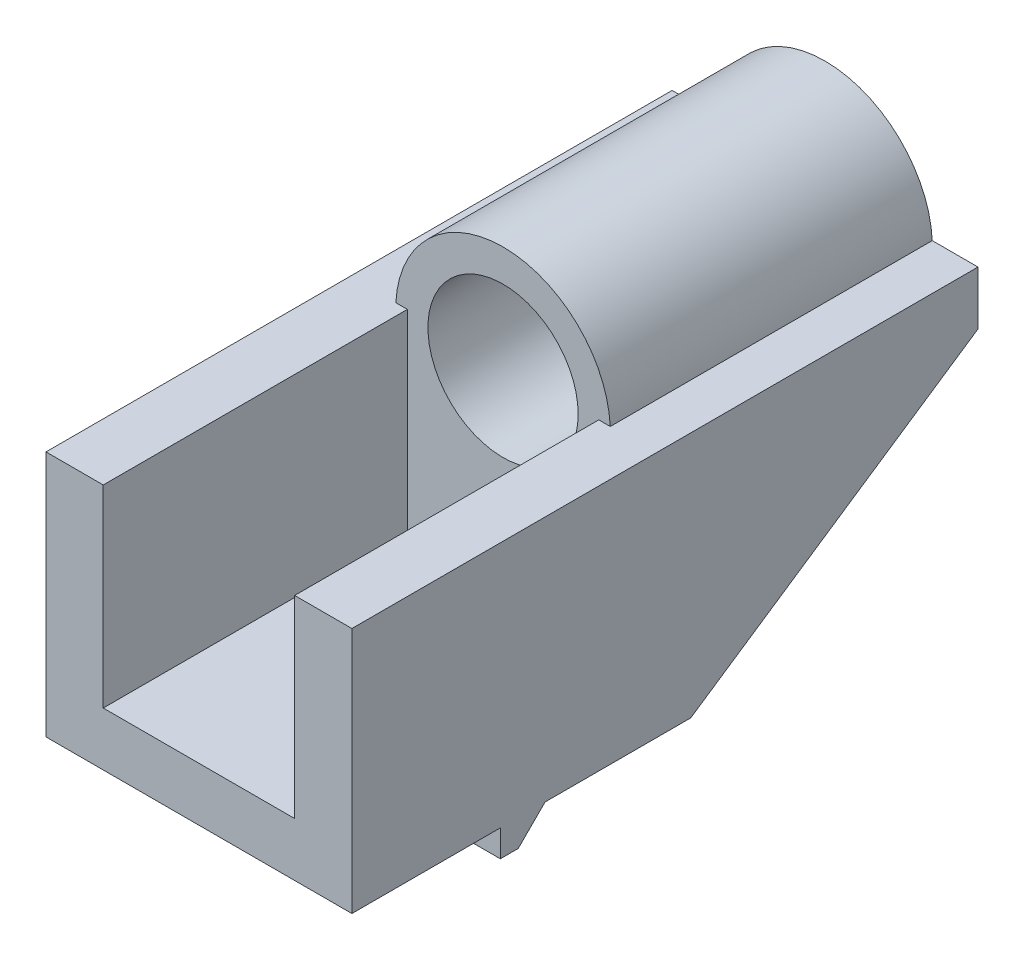
SolidWorks part; units mm, degrees
material "ABS"
ref_plane "Front Plane" through (0, 0, 0) normal (0, 0, 1) x (1, 0, 0)
ref_plane "Top Plane" through (0, 0, 0) normal (0, 1, 0) x (1, 0, 0)
ref_plane "Right Plane" through (0, 0, 0) normal (1, 0, 0) x (0, 0, -1)
sketch "Sketch1" plane through (0, 0, 0) normal (1, 0, 0) x (0, 0, -1)
  line L0 (0, 0) -> (0, -3)
  line L1 (0, -3) -> (-16.0587, -13.8)
  line L2 (-16.0587, -13.8) -> (-35, -13.8)
  line L3 (-35, -13.8) -> (-35, 0)
  line L4 (-35, 0) -> (0, 0)
  dimension "D1" = 35
  dimension "D2" = 3
  dimension "D3" = 13.8
  dimension "D4" = 18.9413
extrude "Boss-Extrude1" add sketch "Sketch1" along normal mid plane 17.1
sketch "Sketch2" plane through (0, 0, 35) normal (0, 0, 1) x (1, 0, 0)
  line L0 (8.55, 0) -> (-8.55, 0) construction
  line L1 (-5.35, 0) -> (5.35, 0)
  line L2 (-5.35, 0) -> (-5.35, -10.8)
  line L3 (-5.35, -10.8) -> (5.35, -10.8)
  line L4 (5.35, 0) -> (5.35, -10.8)
  line L5 (0, -10.8) -> (0, -13.8) construction
  line L6 (8.55, -13.8) -> (-8.55, -13.8) construction
  dimension "D1" = 10.7
  dimension "D2" = 10.8
extrude "Cut-Extrude1" cut sketch "Sketch2" against normal blind 17
sketch "Sketch3" plane through (0, 0, 18) normal (0, 0, 1) x (1, 0, 0)
  line L0 (5.35, 0) -> (-5.35, 0) construction
  circle A0 centre (0, -0.3017) radius 6
  dimension "D1" = 12
  dimension "D2" = 0.3018
extrude "Boss-Extrude2" add sketch "Sketch3" against normal through all
sketch "Sketch4" plane through (0, 0, 18) normal (0, 0, 1) x (1, 0, 0)
  circle A0 centre (0, -0.3017) radius 4.2
  dimension "D1" = 8.4
extrude "Cut-Extrude2" cut sketch "Sketch4" against normal through all
sketch "Sketch8" plane through (8.55, 0, 0) normal (1, 0, 0) x (0, 0, -1)
  line L0 (-26.702, -13.8) -> (-26.702, -15.3)
  line L1 (-35, -13.8) -> (-16.0587, -13.8) construction
  line L2 (-26.702, -15.3) -> (-25.702, -15.3)
  line L3 (-25.702, -15.3) -> (-24.202, -13.8)
  line L4 (-24.202, -13.8) -> (-26.702, -13.8)
  line L5 (-16.0587, -13.8) -> (-15.002, -13.8)
  line L6 (-13, -13.8) -> (-11.046, -10.4288)
  line L7 (-16.0587, -13.8) -> (0, -3) construction
  line L8 (-11.046, -10.4288) -> (-16.0587, -13.8)
  line L9 (-13, -13.8) -> (-14.002, -14.8)
  line L10 (-14.002, -14.8) -> (-15.002, -14.8)
  line L11 (-15.002, -14.8) -> (-15.002, -13.8)
  line L12 (-35, 0) -> (-35, -13.8) construction
  dimension "D1" = 1
  dimension "D2" = 1.5
  dimension "D3" = 2.5
  dimension "D4" = 8.298
  dimension "D5" = 3.0587
  dimension "D6" = 1
  dimension "D7" = 1
  dimension "D8" = 11.7
  dimension "D9" = 165.04
extrude "Boss-Extrude5" add sketch "Sketch8" against normal through all
sketch "Sketch7" plane through (0, -10.8, 0) normal (0, 1, 0) x (1, 0, 0)
  line L0 (0, -25) -> (0, -35) construction
  line L1 (-5.35, -35) -> (5.35, -35) construction
  circle A0 centre (0, -25) radius 2.2
  dimension "D1" = 4.4
  dimension "D2" = 10
extrude "Cut-Extrude3" cut sketch "Sketch7" against normal through all
sketch "Sketch10" plane through (0, 0, 26.702) normal (0, 0, 1) x (1, 0, 0)
  line L1 (-4.053, -13.8) -> (4.053, -13.8)
  line L2 (-4.053, -13.8) -> (-4.053, -15.3)
  line L3 (-4.053, -15.3) -> (4.053, -15.3)
  line L4 (4.053, -13.8) -> (4.053, -15.3)
  line L5 (1.394, -15.3) -> (8.55, -15.3) construction
  line L6 (-8.55, -13.8) -> (-1.394, -13.8) construction
  line L7 (0, -13.8) -> (0, -10.8) construction
  line L8 (8.55, -13.8) -> (-8.55, -13.8) construction
  line L9 (-5.35, -10.8) -> (5.35, -10.8) construction
  dimension "D1" = 8.106
extrude "Cut-Extrude4" cut sketch "Sketch10" against normal up to next
sketch "Sketch11" plane through (0, 0, 15.002) normal (0, 0, 1) x (1, 0, 0)
  line L0 (-8.55, -13.8) -> (8.55, -13.8) construction
  line L1 (-8.55, -14.8) -> (-1.553, -14.8)
  line L2 (-8.55, -14.8) -> (-8.55, -13.8)
  line L3 (-8.55, -13.8) -> (-1.553, -13.8)
  line L4 (-1.553, -14.8) -> (-1.553, -13.8)
  line L6 (8.55, -14.8) -> (1.553, -14.8)
  line L7 (8.55, -14.8) -> (8.55, -13.8)
  line L8 (8.55, -13.8) -> (1.553, -13.8)
  line L9 (1.553, -14.8) -> (1.553, -13.8)
  dimension "D1" = 3.106
extrude "Cut-Extrude5" cut sketch "Sketch11" against normal through all
sketch "Sketch12" plane through (0, -13.8, 0) normal (0, -1, 0) x (1, 0, 0)
  line L0 (-1.553, 13) -> (-5.353, 16.8)
  line L1 (-5.353, 16.8) -> (-5.353, 0)
  line L2 (-5.353, 0) -> (5.353, 0)
  line L3 (5.353, 0) -> (5.353, 16.8)
  line L4 (5.353, 16.8) -> (1.553, 13)
  line L5 (1.553, 13) -> (-1.553, 13)
  line L7 (8.55, 0) -> (5.3591, 0) construction
  dimension "D1" = 3.8
  dimension "D2" = 3.8
  dimension "D3" = 3.8
extrude "Cut-Extrude6" cut sketch "Sketch12" against normal up to surface (10.788 mm away)
sketch "Sketch13" plane through (0, 0, 0) normal (0, 0, -1) x (-1, 0, 0)
  line L0 (-5.3591, -3) -> (-5.353, -10.4288)
  line L1 (-5.353, -10.4288) -> (5.353, -10.4288)
  line L2 (5.353, -10.4288) -> (5.3591, -3)
  arc A0 (-5.3591, -3) -> (5.3591, -3) centre (0, -0.3017) ccw construction
  arc A1 (-5.3591, -3) -> (5.3591, -3) centre (0, -0.3017) ccw
extrude "Cut-Extrude7" cut sketch "Sketch13" against normal up to vertex
sketch "Sketch14" plane through (0, 0, 0) normal (1, 0, 0) x (0, 0, -1)
  line L0 (-13, -13.8) -> (-8.0733, -5.3)
  line L1 (-8.0733, -5.3) -> (-16.8, -5.3)
  line L2 (-13, -13.8) -> (-11.046, -10.4288) construction
  line L3 (-13, -13.8) -> (-16.8, -13.8)
  line L4 (-16.8, -13.8) -> (-16.8, -5.3)
  line L5 (-16.8, -3) -> (-16.8, -10.4288) construction
  dimension "D1" = 8.5
extrude "Boss-Extrude6" add sketch "Sketch14" along normal mid plane 3.106
ref_plane "Plane1" through (-7.4364, -6.5239, 7.4364) normal (0.6009, 0.5271, -0.6009) x (-0.7993, 0.3963, -0.4517)
sketch "Sketch15" plane through (-7.4364, -6.5239, 7.4364) normal (0.6009, 0.5271, -0.6009) x (-0.7993, 0.3963, -0.4517)
  line L0 (-11.246, 0.7337) -> (-11.246, 6.4958)
  line L1 (-11.246, 6.4958) -> (-15.9999, 3.2397)
  line L2 (-15.9999, 3.2397) -> (-11.246, 0.7337)
extrude "Boss-Extrude7" add sketch "Sketch15" against normal up to next
mirror "Mirror1" about plane through (0, 0, 0) normal (1, 0, 0) of "Boss-Extrude7"
sketch "Sketch16" plane through (8.55, 0, 0) normal (1, 0, 0) x (0, 0, -1)
  line L0 (-11.046, -10.4288) -> (-16.0587, -13.8)
  line L1 (-24.202, -13.8) -> (-13, -13.8) construction
  line L2 (-16.0587, -13.8) -> (-13, -13.8)
  line L3 (-13, -13.8) -> (-11.046, -10.4288)
  line L4 (-11.046, -10.4288) -> (0, -3) construction
extrude "Cut-Extrude8" cut sketch "Sketch16" against normal up to next
sketch "Sketch17" plane through (-8.55, 0, 0) normal (-1, 0, 0) x (0, 0, 1)
  line L0 (11.046, -10.4288) -> (16.0587, -13.8)
  line L1 (24.202, -13.8) -> (13, -13.8) construction
  line L2 (16.0587, -13.8) -> (13, -13.8)
  line L3 (13, -13.8) -> (11.046, -10.4288)
  line L4 (11.046, -10.4288) -> (0, -3) construction
extrude "Cut-Extrude9" cut sketch "Sketch17" against normal up to next
